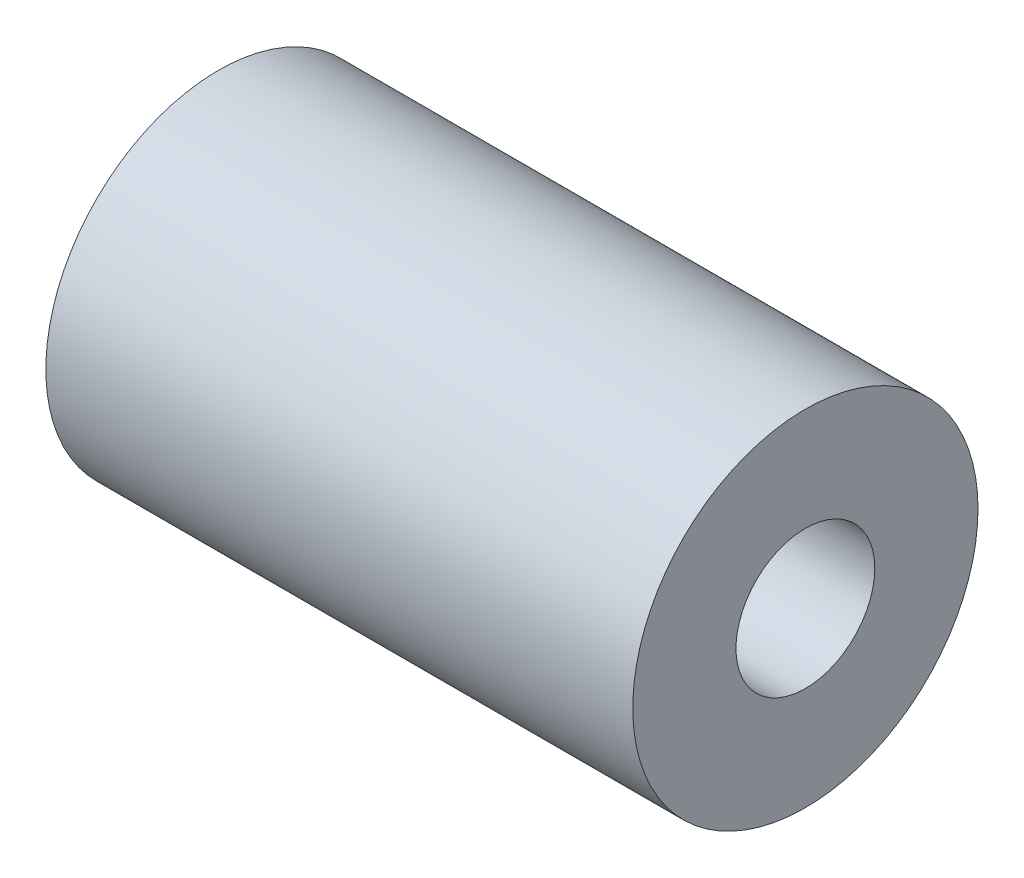
SolidWorks part; units mm, degrees
ref_plane "Front Plane" through (0, 0, 0) normal (0, 0, 1) x (1, 0, 0)
ref_plane "Top Plane" through (0, 0, 0) normal (0, 1, 0) x (1, 0, 0)
ref_plane "Right Plane" through (0, 0, 0) normal (1, 0, 0) x (0, 0, -1)
sketch "Sketch1" plane through (0, 0, 0) normal (1, 0, 0) x (0, 0, -1)
  circle A0 centre (0, 0) radius 2.5527
  circle A1 centre (0, 0) radius 6.35
  dimension "D1" = 5.1054
  dimension "D2" = 12.7
extrude "Boss-Extrude1" add sketch "Sketch1" along normal blind 21.59
